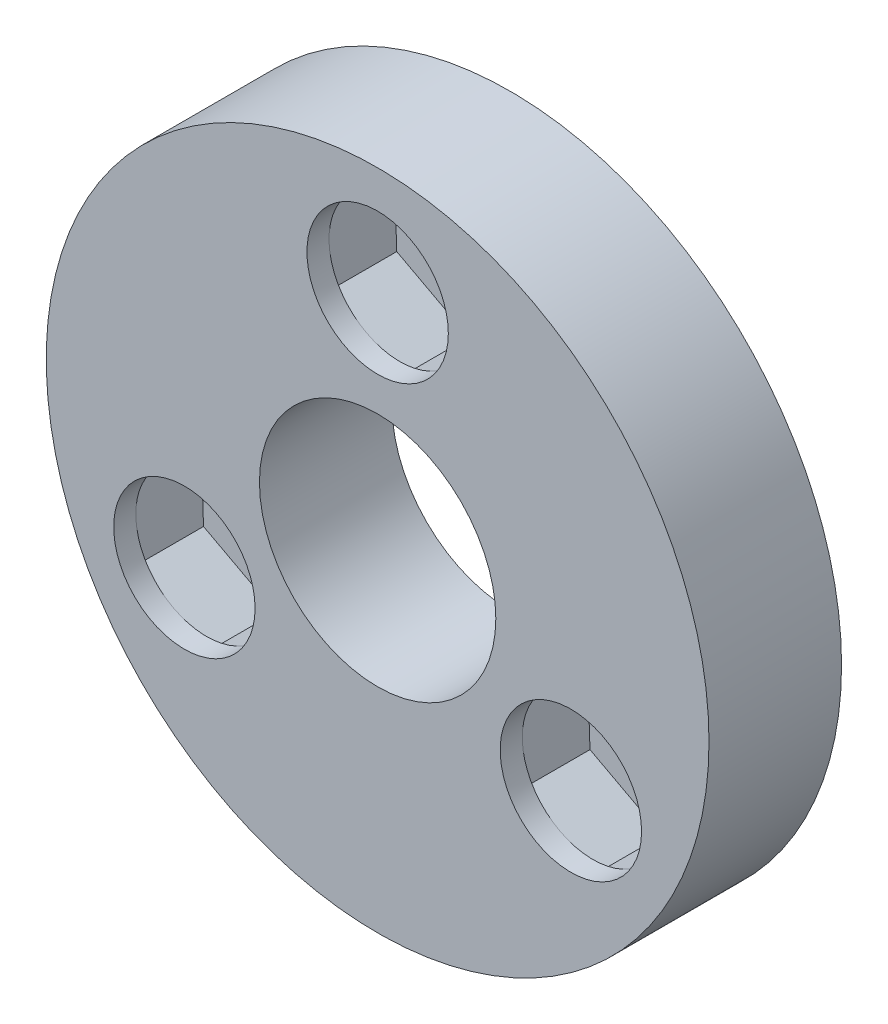
SolidWorks part; units mm, degrees
material "Plain Carbon Steel"
ref_plane "Front Plane" through (0, 0, 0) normal (1, 0, 0) x (0, 1, 0)
ref_plane "Top Plane" through (0, 0, 0) normal (0, 0, 1) x (0, 1, 0)
ref_plane "Right Plane" through (0, 0, 0) normal (0, 1, 0) x (-1, 0, 0)
sketch "Sketch1" plane through (0, 0, 0) normal (0, 0, 1) x (0, 1, 0)
  circle A0 centre (0, 0) radius 15
  dimension "D1" = 30
extrude "Boss-Extrude1" add sketch "Sketch1" along normal blind 6
sketch "Sketch2" plane through (0, 0, 6) normal (0, 0, 1) x (1, 0, 0)
  line L0 (0, 0) -> (0, 15) construction
  line L1 (0, 15) -> (0, 12) construction
  line L2 (0, 12) -> (0, 8.2) construction
  line L3 (8.8739, -8.7429) -> (12.0085, -6.7864)
  line L4 (3.1346, 12.0564) -> (-0.127, 13.7929)
  line L5 (-0.127, 13.7929) -> (-3.2616, 11.8364)
  line L6 (-3.2616, 11.8364) -> (-3.1346, 8.1436)
  line L7 (-3.1346, 8.1436) -> (0.127, 6.4071)
  line L8 (0.127, 6.4071) -> (3.2616, 8.3636)
  line L9 (3.2616, 8.3636) -> (3.1346, 12.0564)
  line L10 (12.0085, -6.7864) -> (11.8815, -3.0936)
  line L11 (11.8815, -3.0936) -> (8.6199, -1.3571)
  line L12 (8.6199, -1.3571) -> (5.4852, -3.3136)
  line L13 (5.4852, -3.3136) -> (5.6122, -7.0064)
  line L14 (5.6122, -7.0064) -> (8.8739, -8.7429)
  line L15 (0, 0) -> (12.9904, -7.5) construction
  line L16 (12.9904, -7.5) -> (10.3923, -6) construction
  line L17 (10.3923, -6) -> (7.1014, -4.1) construction
  line L18 (-12.0085, -3.3136) -> (-11.8815, -7.0064)
  line L19 (-11.8815, -7.0064) -> (-8.6199, -8.7429)
  line L20 (-8.6199, -8.7429) -> (-5.4852, -6.7864)
  line L21 (-5.4852, -6.7864) -> (-5.6122, -3.0936)
  line L22 (-5.6122, -3.0936) -> (-8.8739, -1.3571)
  line L23 (-8.8739, -1.3571) -> (-12.0085, -3.3136)
  line L24 (0, 0) -> (-12.9904, -7.5) construction
  line L25 (-12.9904, -7.5) -> (-10.3923, -6) construction
  line L26 (-10.3923, -6) -> (-7.1014, -4.1) construction
  circle A0 centre (0, 0) radius 15 construction
  circle A4 centre (0, 10.1) radius 3.2 construction
  circle A6 centre (8.7469, -5.05) radius 3.2 construction
  circle A8 centre (-8.7469, -5.05) radius 3.2 construction
  point P9 (0, 9.6)
  point P10 (0, 9.6)
  point P11 (0, 0)
  point P16 (0, 0)
  point P49 (0, 0)
  dimension "D1" = 3
  dimension "D2" = 3.8
  dimension "D4" = 3
sketch "Sketch3" plane through (0, 0, 6) normal (0, 0, 1) x (1, 0, 0)
  circle A0 centre (0, 0) radius 8.5
  dimension "D1" = 17
sketch "Sketch5" plane through (0, 0, 0) normal (0, 0, -1) x (1, 0, 0)
  circle A0 centre (0, 0) radius 5.35
  dimension "D1" = 10.7
extrude "Cut-Extrude2" cut sketch "Sketch5" against normal blind 11.5
extrude "Cut-Extrude3" cut sketch "Sketch2" against normal blind 3 from offset 1 offset against normal yes
sketch "Sketch7" plane through (0, 0, 6) normal (0, 0, 1) x (1, 0, 0)
  circle A0 centre (0, 10.1) radius 3.2
  circle A1 centre (8.7469, -5.05) radius 3.2
  circle A2 centre (-8.7469, -5.05) radius 3.2
  point P3 (0, 0)
  point P10 (0, 0)
  dimension "D1" = 3.2
  dimension "D2" = 3
extrude "Cut-Extrude4" cut sketch "Sketch7" against normal blind 2.5 contours A1 | A0 | A2
